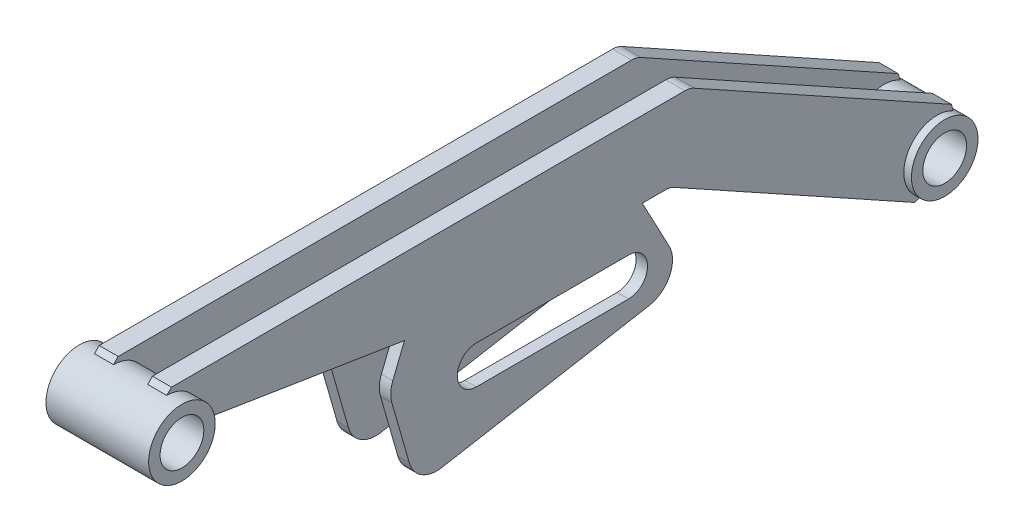
SolidWorks part; units mm, degrees
other "Element opisowy1"
other "Element opisowy2"
other "Element opisowy3"
other "Element opisowy4"
other "Element opisowy5"
other "Element opisowy6"
other "Element opisowy7"
other "Element opisowy8"
other "Element opisowy9"
other "Element opisowy10"
other "Element opisowy11"
other "Element opisowy12"
other "Element opisowy13"
other "Folder spoin"
other "Ścieg spoiny5"
other "Ścieg spoiny6"
other "Ścieg spoiny7"
other "Ścieg spoiny8"
other "Ścieg spoiny9"
other "Ścieg spoiny10"
other "Ścieg spoiny11"
other "Ścieg spoiny12"
other "Ścieg spoiny1"
other "Ścieg spoiny2"
other "Ścieg spoiny3"
other "Ścieg spoiny4"
other "Ścieg spoiny13"
material "1.0044 (S275JR)"
ref_plane "Płaszczyzna przednia" through (0, 0, 0) normal (0, 0, 1) x (1, 0, 0)
ref_plane "Płaszczyzna górna" through (0, 0, 0) normal (0, 1, 0) x (1, 0, 0)
ref_plane "Płaszczyzna prawa" through (0, 0, 0) normal (1, 0, 0) x (0, 0, -1)
sketch "Szkic1" plane through (0, 0, 0) normal (1, 0, 0) x (0, 0, -1)
  line L0 (0, 0) -> (272.5, 0)
  line L1 (272.5, 0) -> (410.0096, -76.2228)
  line L2 (410.0096, -76.2228) -> (410.9842, -79.6214)
  line L3 (410.9842, -79.6214) -> (394.0158, -110.2331)
  line L4 (394.0158, -110.2331) -> (390.6173, -111.2076)
  line L5 (390.6173, -111.2076) -> (262.1553, -40)
  line L6 (262.1553, -40) -> (122.5, -40)
  line L7 (122.5, -40) -> (-2.5, -20)
  line L8 (-2.5, -20) -> (-2.5, -2.5)
  line L9 (-2.5, -2.5) -> (0, 0)
  point P14 (402.5, -94.9273)
  dimension "D1" = 45
  dimension "D2" = 17.5
  dimension "D3" = 40
  dimension "D4" = 125
  dimension "D5" = 40
  dimension "D6" = 151
  dimension "D7" = 130
  dimension "D8" = 35
  dimension "D9" = 45
  dimension "D10" = 45
  dimension "D11" = 275
  dimension "D12" = 20
extrude "Dodanie-wyciągnięcie1" add sketch "Szkic1" along normal blind 10
ref_plane "Płaszczyzna1" through (-9, 0, 0) normal (-1, 0, 0) x (0, 0, 1)
mirror "Lustro3" about plane through (-9, 0, 0) normal (-1, 0, 0) of bodies 101
sketch "Szkic2" plane through (10, 0, 0) normal (1, 0, 0) x (0, 0, -1)
  line L0 (-2.5, -2.5) -> (-2.5, -20) construction
  line L1 (272.5, 0) -> (0, 0) construction
  circle A0 centre (-2.5, -20) radius 17.5
  point P4 (0, 0)
  dimension "D1" = 35
  dimension "D2" = 20
extrude "Dodanie-wyciągnięcie2" add sketch "Szkic2" along normal blind 8 and the other way blind 46
sketch "Szkic3" plane through (10, 0, 0) normal (1, 0, 0) x (0, 0, -1)
  line L0 (394.0158, -110.2331) -> (410.9842, -79.6214) construction
  circle A0 centre (402.5, -94.9273) radius 17.5
  dimension "D1" = 35
extrude "Dodanie-wyciągnięcie3" add sketch "Szkic3" along normal blind 4 and the other way blind 42
sketch "Szkic4" plane through (18, 0, 0) normal (1, 0, 0) x (0, 0, -1)
  circle A0 centre (-2.5, -20) radius 11.5
  dimension "D1" = 23
extrude "Wytnij-wyciągnięcie1" cut sketch "Szkic4" against normal up to next
sketch "Szkic5" plane through (14, 0, 0) normal (1, 0, 0) x (0, 0, -1)
  circle A0 centre (402.5, -94.9273) radius 11.5
  dimension "D1" = 23
extrude "Wytnij-wyciągnięcie2" cut sketch "Szkic5" against normal up to next
fillet "Zaokrąglenie2" radius 10 4 edges at (-23, -40, -262.1553) (5, -40, -262.1553) (-23, 0, -272.5) (5, 0, -272.5)
sketch "Szkic6" plane through (-28, 0, 0) normal (-1, 0, 0) x (0, 0, 1)
  line L0 (-122.5, -40) -> (-116.3543, -55.2112)
  line L1 (-14.7802, -22.7648) -> (-122.5, -40) construction
  line L2 (-122.5, -40) -> (-259.5691, -40) construction
  line L3 (-115.8431, -64.9648) -> (-125.034, -97.0171)
  line L4 (-142.0576, -107.6547) -> (-251.0187, -88.4419)
  line L5 (-261.6582, -66.6277) -> (-247.5, -40)
  line L6 (-247.5, -40) -> (-122.5, -40)
  line L7 (-86.355, -131.8554) -> (-276.9477, -131.8554) construction
  arc A0 (-251.0187, -88.4419) -> (-261.6582, -66.6277) centre (-248.414, -73.6698) cw
  arc A1 (-125.034, -97.0171) -> (-142.0576, -107.6547) centre (-139.4529, -92.8826) cw
  arc A2 (-116.3543, -55.2112) -> (-115.8431, -64.9648) centre (-130.262, -60.8303) cw
  point P21 (-128.7567, -110)
  point P24 (-114.4195, -60)
  dimension "D8" = 15
  dimension "D9" = 15
  dimension "D1" = 118
  dimension "D2" = 112
  dimension "D3" = 218
  dimension "D4" = 10
  dimension "D5" = 125
  dimension "D6" = 70
  dimension "D7" = 20
extrude "Dodanie-wyciągnięcie4" add sketch "Szkic6" against normal blind 6 separate body
mirror "Lustro4" about plane through (-9, 0, 0) normal (-1, 0, 0) of "Dodanie-wyciągnięcie4"
sketch "Szkic17" plane through (-9, 0, 0) normal (-1, 0, 0) x (0, 0, 1)
  line L0 (-240.262, -70) -> (-160.262, -70) construction
  line L1 (-240.262, -60) -> (-160.262, -60)
  line L2 (-240.262, -80) -> (-160.262, -80)
  line L3 (-122.5, -40) -> (-259.5691, -40) construction
  arc A0 (-240.262, -60) -> (-240.262, -80) centre (-240.262, -70) ccw
  arc A1 (-160.262, -80) -> (-160.262, -60) centre (-160.262, -70) ccw
  arc A4 (-115.8431, -64.9648) -> (-116.3543, -55.2112) centre (-130.262, -60.8303) ccw construction
  point P2 (-200.262, -70)
  dimension "D2" = 100
  dimension "D4" = 35
  dimension "D1" = 20
  dimension "D3" = 20
extrude "Wytnij-wyciągnięcie6" cut sketch "Szkic17" against normal through all and the other way through all
ref_plane "Płaszczyzna2" through (0, -70, 0) normal (0, -1, 0) x (-1, 0, 0)
